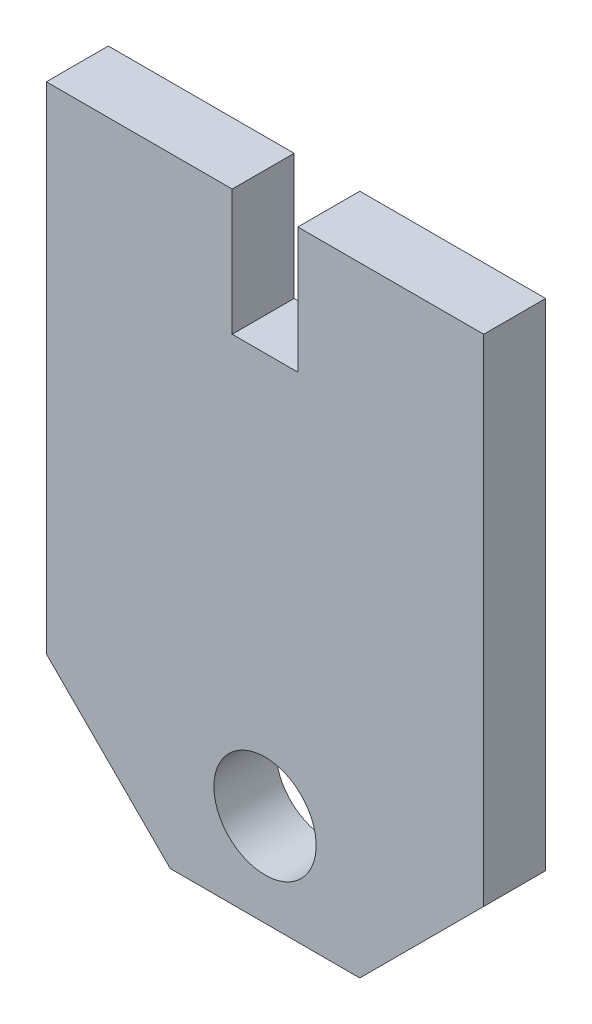
SolidWorks part; units mm, degrees
ref_plane "Front Plane" through (0, 0, 0) normal (0, 0, 1) x (1, 0, 0)
ref_plane "Top Plane" through (0, 0, 0) normal (0, 1, 0) x (1, 0, 0)
ref_plane "Right Plane" through (0, 0, 0) normal (1, 0, 0) x (0, 0, -1)
ref_plane "Plane1" through (0, 0, -25) normal (0, 0, -1) x (-1, 0, 0)
sketch "Sketch2" plane through (0, 0, -25) normal (0, 0, 1) x (1, 0, 0)
  line L0 (227.6381, -115) -> (237.6381, -115) construction
  line L1 (237.6381, -115) -> (237.6381, -84.7) construction
  line L2 (237.6381, -84.7) -> (227.6381, -84.7) construction
  line L3 (227.6381, -84.7) -> (227.6381, -115) construction
  line L4 (227.6381, -115) -> (237.6381, -115)
  line L5 (237.6381, -115) -> (237.6381, -84.7)
  line L6 (237.6381, -84.7) -> (227.6381, -84.7)
  line L7 (227.6381, -84.7) -> (227.6381, -115)
  line L9 (237.6381, -115) -> (237.6381, -84.7) construction
  line L10 (237.6381, -84.7) -> (227.6381, -84.7) construction
  line L11 (227.6381, -84.7) -> (227.6381, -115) construction
  line L12 (227.3381, -85) -> (227.3381, -115) construction
  line L13 (237.6381, -85) -> (227.6381, -85) construction
  line L14 (227.3381, -85) -> (237.9381, -85)
  line L15 (227.6381, -84.7) -> (227.6381, -115) construction
  line L16 (237.9381, -115) -> (237.9381, -85) construction
  line L17 (227.3381, -84.7) -> (227.3381, -115) construction
  line L18 (237.9381, -115) -> (237.9381, -84.7) construction
  line L19 (227.3381, -85) -> (227.3381, -64.7)
  line L20 (237.9381, -85) -> (237.9381, -64.7)
  line L21 (227.3381, -64.7) -> (197.3381, -64.7)
  line L22 (237.9381, -64.7) -> (267.9381, -64.7)
  line L23 (267.9381, -64.7) -> (267.9381, -144.7)
  line L24 (197.3381, -64.7) -> (197.3381, -144.7)
  line L25 (217.3381, -164.7) -> (247.9381, -164.7)
  line L26 (197.3381, -144.7) -> (217.3381, -164.7)
  line L27 (267.9381, -144.7) -> (247.9381, -164.7)
  line L28 (232.6381, -115) -> (232.6381, -404.7) construction
  line L45 (227.6381, -115) -> (237.6381, -115) construction
  line L46 (227.6381, -115) -> (237.6381, -115)
  circle A0 centre (232.6381, -259.85) radius 10.5
  circle A1 centre (232.6381, -149.7) radius 8.25
  point P13 (232.6381, -85)
  point P15 (227.6381, -84.7)
  point P18 (237.6381, -84.7)
  point P21 (232.6381, -85)
  point P25 (267.9381, -164.7)
  point P26 (197.3381, -164.7)
  dimension "D10" = 15
  dimension "D4" = 30
  dimension "D6" = 20.3
  dimension "D7" = 20.3
  dimension "D8" = 30
  dimension "D9" = 100
  dimension "D1" = 0
  dimension "D2" = 0
  dimension "D3" = 0.3
  dimension "D5" = 0.3
extrude "Boss-Extrude1" add sketch "Sketch2" along normal mid plane 10
